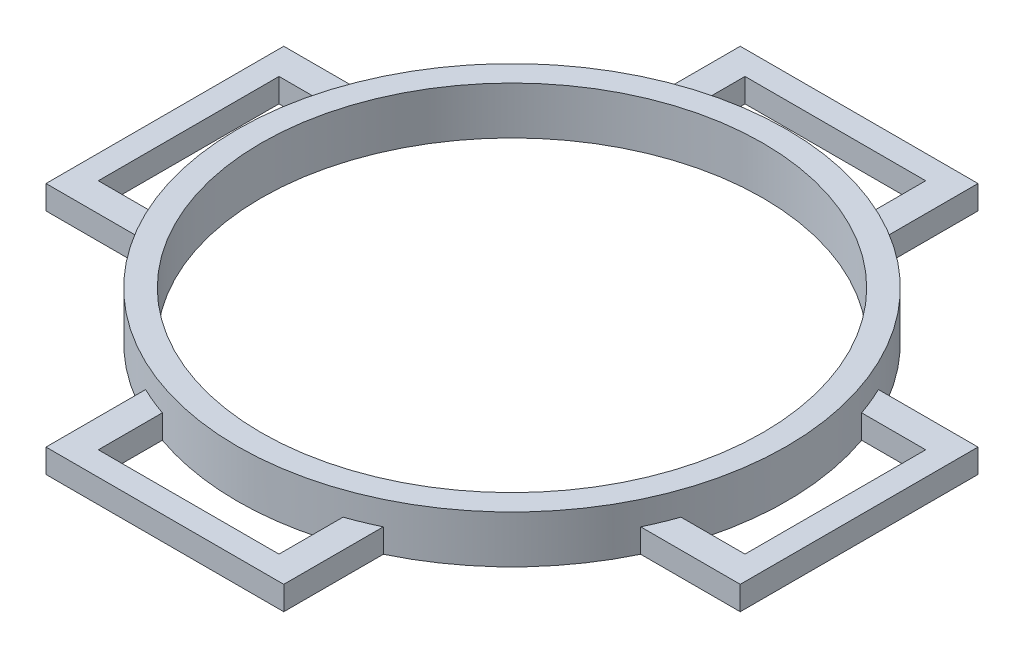
SolidWorks part; units mm, degrees
ref_plane "Alzado" through (0, 0, 0) normal (0, 0, 1) x (1, 0, 0)
ref_plane "Planta" through (0, 0, 0) normal (0, 1, 0) x (1, 0, 0)
ref_plane "Vista lateral" through (0, 0, 0) normal (1, 0, 0) x (0, 0, -1)
sketch "Croquis1" plane through (0, 0, 0) normal (0, 0, 1) x (1, 0, 0)
  line L0 (0, 18.4725) -> (0, -18.4498) construction
  line L2 (11.55, -1) -> (10.55, -1)
  line L3 (11.55, -1) -> (11.55, 1)
  line L4 (11.55, 1) -> (10.55, 1)
  line L5 (10.55, -1) -> (10.55, 1)
  line L6 (11.55, -1) -> (10.55, 1) construction
  line L7 (11.55, 1) -> (10.55, -1) construction
  point P3 (11.05, 0)
  point P8 (0, 0)
  point P9 (0, 0)
  dimension "D1" = 11.05
  dimension "D2" = 1
  dimension "D3" = 2
revolve "Revolución1" add sketch "Croquis1" angle 360 about L0
sketch "Croquis2" plane through (0, 0, 0) normal (0, 1, 0) x (1, 0, 0)
  line L0 (-5, -10.4117) -> (-5, -14.6)
  line L1 (-5, -14.6) -> (5, -14.6)
  line L2 (5, -14.6) -> (5, -10.4117)
  line L3 (-3.8, -10.907) -> (-3.8, -13.6)
  line L4 (-3.8, -13.6) -> (3.8, -13.6)
  line L5 (3.8, -13.6) -> (3.8, -10.907)
  line L6 (-5, -10.4117) -> (-3.8, -10.4117)
  line L7 (-3.8, -10.4117) -> (-3.8, -10.907)
  line L8 (5, -10.4117) -> (3.8, -10.4117)
  line L9 (3.8, -10.4117) -> (3.8, -10.907)
  circle A0 centre (0, 0) radius 11.55 construction
  point P8 (0, -14.6)
  point P11 (0, -13.6)
  dimension "D2" = 13.6
  dimension "D1" = 10
  dimension "D3" = 1
  dimension "D4" = 1.2
extrude "Saliente-Extruir1" add sketch "Croquis2" along normal blind 1 from surface at -1 starting at face at (0, -1, 11.55)
sketch "Croquis3" plane through (0, 0, 0) normal (0, 0, 1) x (1, 0, 0)
  line L0 (0, 8.5059) -> (0, -9.7005) construction
pattern_circular "MatrizC1" count 4 every 90 about axis through (0, 0, 0) along (0, 1, 0) of "Saliente-Extruir1"
